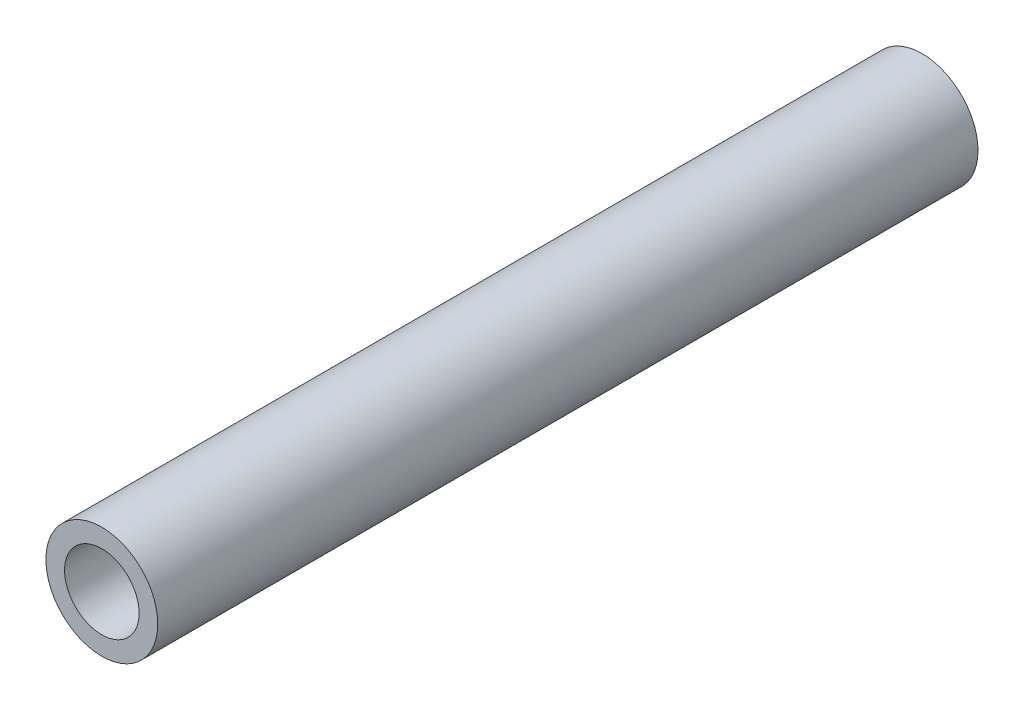
SolidWorks part; units mm, degrees
material "铝青铜"
ref_plane "前视基准面" through (0, 0, 0) normal (0, 0, 1) x (1, 0, 0)
ref_plane "上视基准面" through (0, 0, 0) normal (0, 1, 0) x (1, 0, 0)
ref_plane "右视基准面" through (0, 0, 0) normal (1, 0, 0) x (0, 0, -1)
sketch "草图1" plane through (0, 0, 0) normal (0, 0, 1) x (1, 0, 0)
  circle A0 centre (0, 0) radius 2
  circle A1 centre (0, 0) radius 3
extrude "凸台-拉伸1" add sketch "草图1" along normal blind 44
